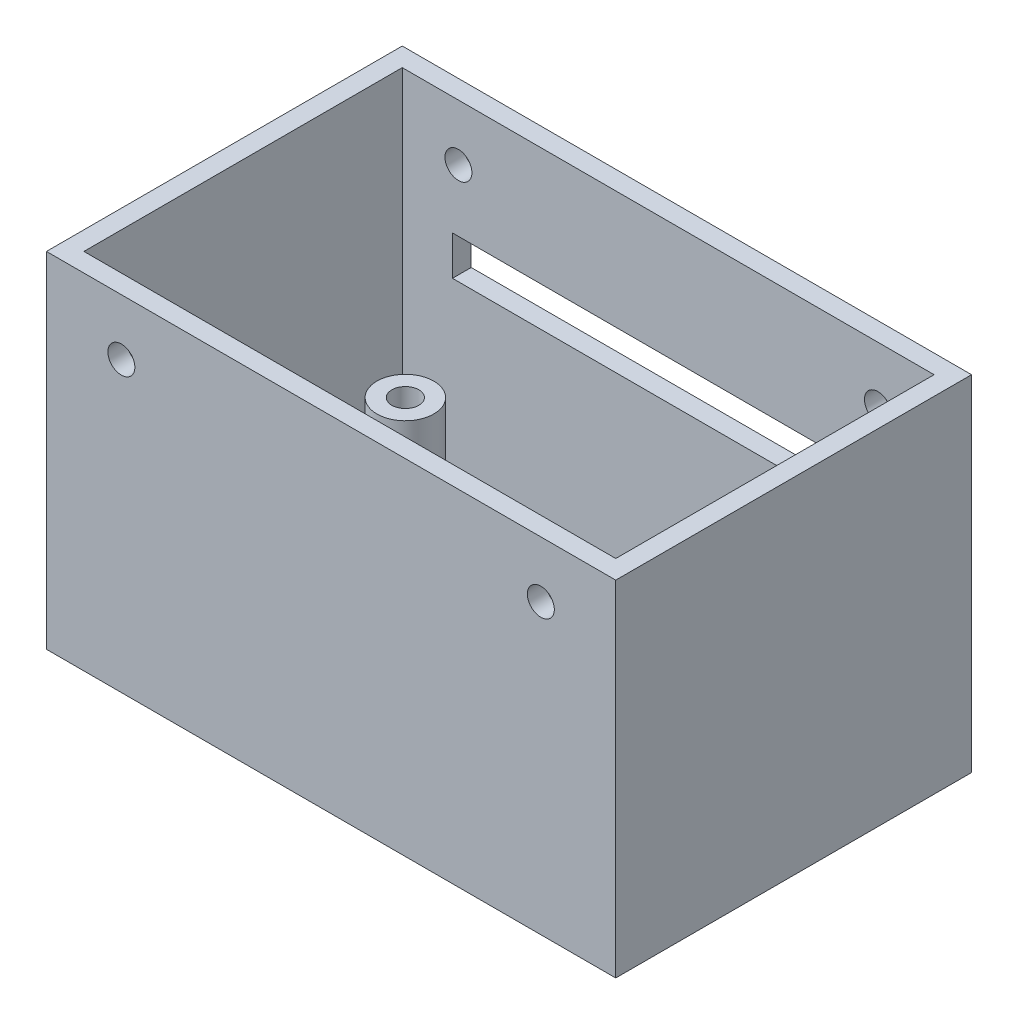
SolidWorks part; units mm, degrees
ref_plane "Front Plane" through (0, 0, 0) normal (0, 0, 1) x (1, 0, 0)
ref_plane "Top Plane" through (0, 0, 0) normal (0, 1, 0) x (1, 0, 0)
ref_plane "Right Plane" through (0, 0, 0) normal (1, 0, 0) x (0, 0, -1)
sketch "Sketch1" plane through (0, 0, 0) normal (0, 1, 0) x (1, 0, 0)
  line L1 (0, 0) -> (152, 0)
  line L2 (0, 0) -> (0, 95)
  line L3 (0, 95) -> (152, 95)
  line L4 (152, 0) -> (152, 95)
  dimension "D1" = 95
  dimension "D2" = 152
extrude "Boss-Extrude2" add sketch "Sketch1" along normal blind 92
sketch "Sketch3" plane through (0, 92, 0) normal (0, 1, 0) x (1, 0, 0)
  line L8 (5, 90) -> (5, 5)
  line L9 (5, 5) -> (147, 5)
  line L10 (147, 5) -> (147, 90)
  line L11 (147, 90) -> (5, 90)
  line L12 (5, 90) -> (5, 5)
  line L13 (5, 5) -> (147, 5)
  line L14 (147, 5) -> (147, 90)
  line L15 (147, 90) -> (5, 90)
  dimension "D1" = 5
extrude "Cut-Extrude2" cut sketch "Sketch3" against normal blind 86
sketch "Sketch5" plane through (0, 6, 0) normal (0, 1, 0) x (1, 0, 0)
  circle A1 centre (20.8453, 18.5936) radius 3.6
  circle A2 centre (20.8453, 18.5936) radius 7.6
  circle A4 centre (21.0993, 74.7276) radius 3.6
  circle A5 centre (21.0993, 74.7276) radius 7.6
  circle A6 centre (129.3033, 17.0696) radius 3.6
  circle A7 centre (129.3033, 17.0696) radius 7.6
  circle A8 centre (129.0493, 75.2356) radius 3.6
  circle A9 centre (129.0493, 75.2356) radius 7.6
extrude "Boss-Extrude7" add sketch "Sketch5" along normal blind 25.4
sketch "Sketch8" plane through (0, 0, 0) normal (0, 0, 1) x (1, 0, 0)
  circle A0 centre (20, 77) radius 3.6
  circle A1 centre (132, 77) radius 3.6
extrude "Cut-Extrude3" cut sketch "Sketch8" against normal through all
sketch "Sketch10" plane through (0, 0, 0) normal (0, -1, 0) x (1, 0, 0)
  circle A1 centre (35.4896, -46.4018) radius 5
  circle A2 centre (115.4896, -46.4018) radius 5
  point P2 (70.1431, -4.6712)
  point P5 (0, 0)
extrude "Cut-Extrude7" cut sketch "Sketch10" against normal through all contours A1 | A2
sketch "Sketch13" plane through (0, 0, -95) normal (0, 0, -1) x (-1, 0, 0)
  line L1 (-133.8371, 60.4812) -> (-18.4069, 60.4812)
  line L2 (-133.8371, 60.4812) -> (-133.8371, 49.9876)
  line L3 (-133.8371, 49.9876) -> (-18.4069, 49.9876)
  line L4 (-18.4069, 60.4812) -> (-18.4069, 49.9876)
extrude "Cut-Extrude8" cut sketch "Sketch13" against normal blind 10
